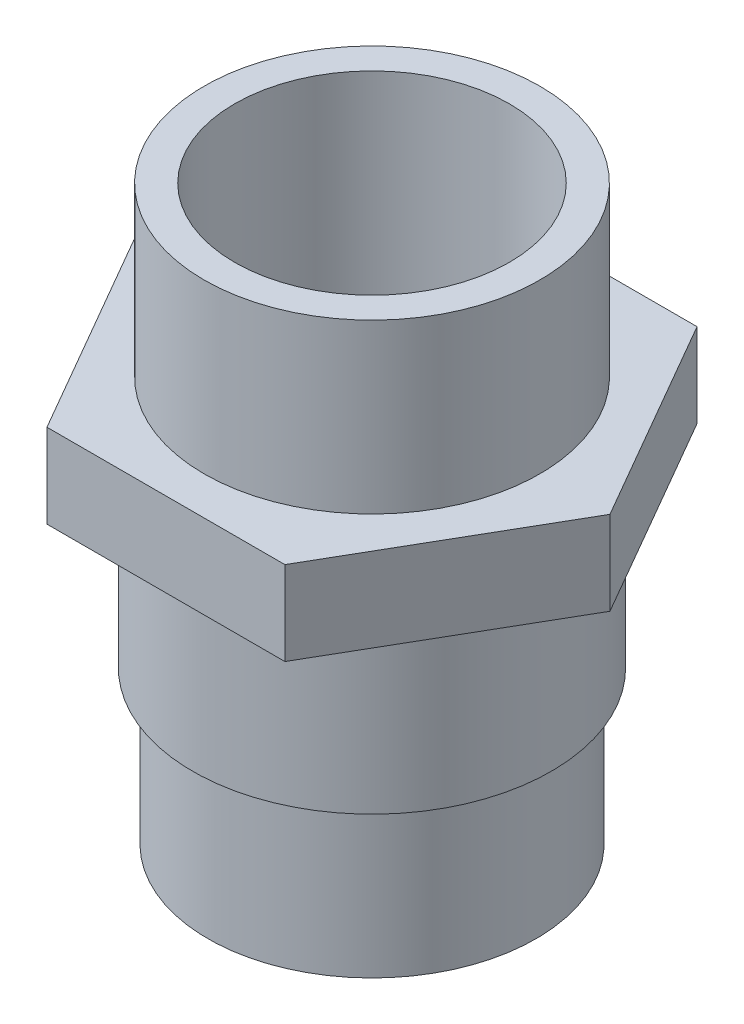
SolidWorks part; units mm, degrees
material "PVC hart"
ref_plane "Ebene vorne" through (0, 0, 0) normal (0, 0, 1) x (1, 0, 0)
ref_plane "Ebene oben" through (0, 0, 0) normal (0, 1, 0) x (1, 0, 0)
ref_plane "Ebene rechts" through (0, 0, 0) normal (1, 0, 0) x (0, 0, -1)
sketch "Skizze1" plane through (0, 0, 0) normal (0, 1, 0) x (1, 0, 0)
  circle A0 centre (0, 0) radius 11
  circle A1 centre (0, 0) radius 9
  dimension "D1" = 18
  dimension "D2" = 22
extrude "Aufsatz-Linear austragen1" add sketch "Skizze1" along normal blind 11
sketch "Skizze2" plane through (0, 0, 0) normal (0, -1, 0) x (1, 0, 0)
  line L1 (15.5885, 0) -> (7.7942, 13.5)
  line L2 (7.7942, 13.5) -> (-7.7942, 13.5)
  line L3 (-7.7942, 13.5) -> (-15.5885, 0)
  line L4 (-15.5885, 0) -> (-7.7942, -13.5)
  line L5 (-7.7942, -13.5) -> (7.7942, -13.5)
  line L6 (7.7942, -13.5) -> (15.5885, 0)
  circle A0 centre (0, 0) radius 9
  circle A1 centre (0, 0) radius 9 construction
  circle A2 centre (0, 0) radius 13.5 construction
  dimension "D1" = 27
extrude "Aufsatz-Linear austragen2" add sketch "Skizze2" along normal blind 5.5
sketch "Skizze3" plane through (0, -5.5, 0) normal (0, -1, 0) x (1, 0, 0)
  circle A0 centre (0, 0) radius 9
  circle A1 centre (0, 0) radius 9 construction
  circle A2 centre (0, 0) radius 11.75
  dimension "D1" = 23.5
extrude "Aufsatz-Linear austragen3" add sketch "Skizze3" along normal blind 11
sketch "Skizze4" plane through (0, -16.5, 0) normal (0, -1, 0) x (1, 0, 0)
  circle A0 centre (0, 0) radius 7
  circle A1 centre (0, 0) radius 10.75
  dimension "D1" = 21.5
  dimension "D2" = 14
extrude "Aufsatz-Linear austragen4" add sketch "Skizze4" along normal blind 10
